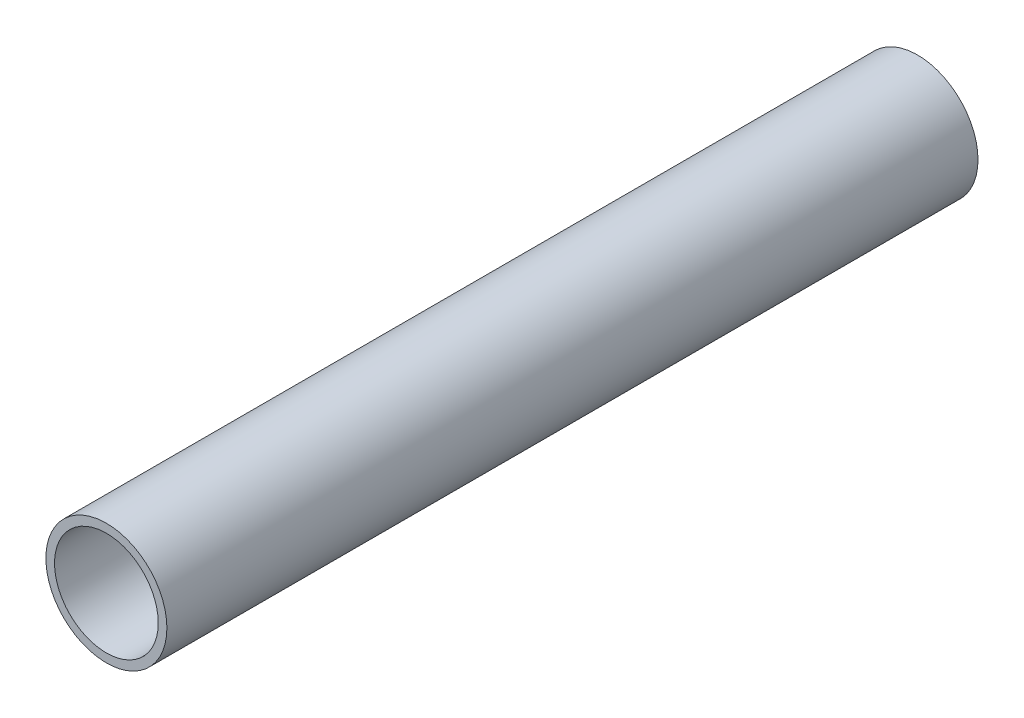
SolidWorks part; units mm, degrees
material "Thornel VCB-20 Carbon Cloth"
ref_plane "Front Plane" through (0, 0, 0) normal (0, 0, 1) x (1, 0, 0)
ref_plane "Top Plane" through (0, 0, 0) normal (0, 1, 0) x (1, 0, 0)
ref_plane "Right Plane" through (0, 0, 0) normal (1, 0, 0) x (0, 0, -1)
sketch "Sketch1" plane through (0, 0, 0) normal (0, 0, 1) x (1, 0, 0)
  circle A0 centre (0, 0) radius 9.525
  circle A1 centre (0, 0) radius 11.1125
  dimension "D1" = 19.05
  dimension "D2" = 22.225
extrude "Boss-Extrude1" add sketch "Sketch1" along normal mid plane 148.971
